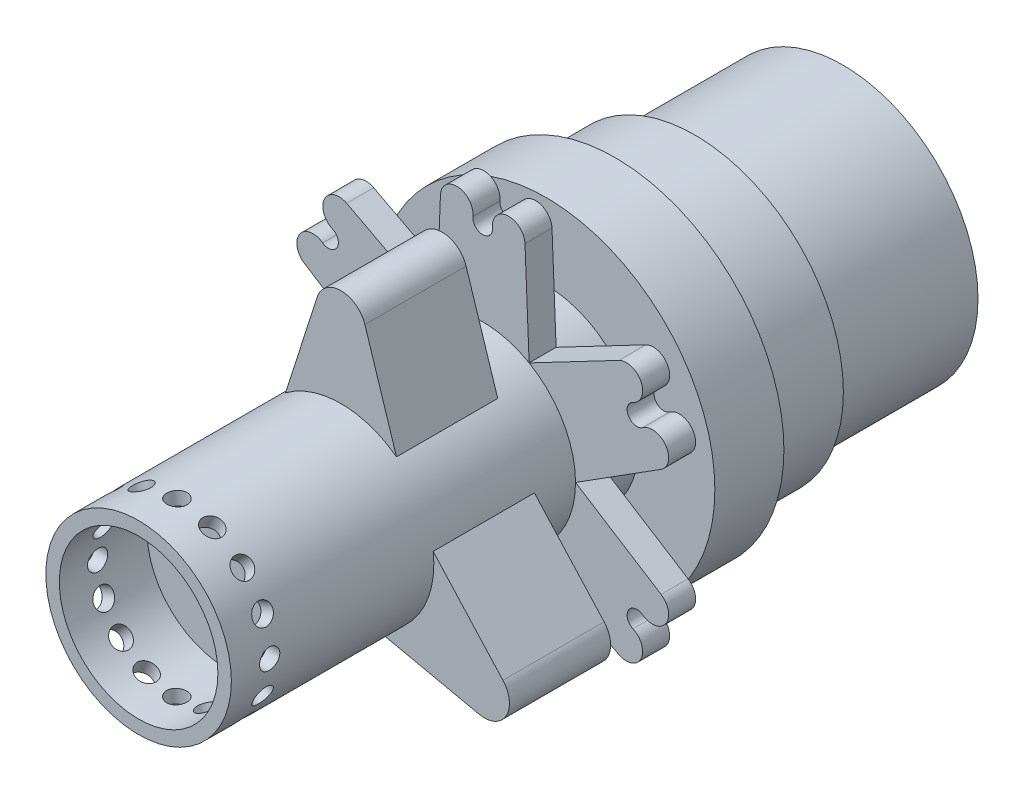
SolidWorks part; units mm, degrees
ref_plane "Front Plane" through (0, 0, 0) normal (0, 0, 1) x (1, 0, 0)
ref_plane "Top Plane" through (0, 0, 0) normal (0, 1, 0) x (1, 0, 0)
ref_plane "Right Plane" through (0, 0, 0) normal (1, 0, 0) x (0, 0, -1)
sketch "Sketch1" plane through (0, 0, 0) normal (0, 0, 1) x (1, 0, 0)
  circle A0 centre (0, 0) radius 17.4625
  dimension "D1" = 34.925
extrude "Boss-Extrude1" add sketch "Sketch1" along normal blind 132.588
ref_axis "Axis1" through (0, 0, 187.0777) along (0, 0, -1)
ref_plane "Wheel Center Mount Plane" through (0, 0, 94.488) normal (0, 0, 1) x (1, 0, 0)
ref_plane "Brake Rotor Mount Plane" through (0, 0, 62.738) normal (0, 0, 1) x (1, 0, 0)
sketch "Sketch3" plane through (0, 0, 94.488) normal (0, 0, 1) x (1, 0, 0)
  line L0 (10.4424, 13.9962) -> (4.4896, 32.5879)
  line L1 (-10.4424, 13.9962) -> (-4.4896, 32.5879)
  line L2 (17.3423, 2.0453) -> (30.4667, -12.4058)
  line L3 (6.8999, -16.0415) -> (25.9771, -20.182)
  line L4 (-6.8999, -16.0415) -> (-25.9771, -20.182)
  line L5 (-17.3423, 2.0453) -> (-30.4667, -12.4058)
  line L6 (0, 0) -> (10.4424, 13.9962) construction
  line L7 (0, 0) -> (6.8999, -16.0415) construction
  arc A0 (4.4896, 32.5879) -> (-4.4896, 32.5879) centre (0, 31.1504) ccw
  circle A1 centre (0, 0) radius 17.4625
  arc A2 (10.4424, 13.9962) -> (-10.4424, 13.9962) centre (0, 0) ccw
  circle A3 centre (0, 0) radius 17.4625 construction
  arc A4 (25.9771, -20.182) -> (30.4667, -12.4058) centre (26.977, -15.5752) ccw
  arc A5 (-30.4667, -12.4058) -> (-25.9771, -20.182) centre (-26.977, -15.5752) ccw
  arc A6 (-17.3423, 2.0453) -> (-6.8999, -16.0415) centre (0, 0) ccw
  arc A7 (6.8999, -16.0415) -> (17.3423, 2.0453) centre (0, 0) ccw
  dimension "D3" = 120
  dimension "D1" = 0
  dimension "D2" = 3
extrude "Boss-Extrude2" add sketch "Sketch3" against normal blind 19.05 contours A7 L3 A4 L2 | A2 L0 A0 L1 | L5 A5 L4 A6
sketch "Sketch4" plane through (0, 0, 62.738) normal (0, 0, 1) x (1, 0, 0)
  line L0 (8.7313, 15.123) -> (7.9569, 34.1622)
  line L1 (0, 0) -> (0, 40.5034) construction
  line L2 (-4.3369, 31.6625) -> (4.3369, 31.6625) construction
  line L3 (-8.7312, 15.123) -> (-7.9569, 34.1622)
  line L4 (17.4625, 0) -> (33.5638, 10.1902)
  line L5 (8.7313, 15.123) -> (25.6068, 23.972)
  line L6 (8.7313, -15.123) -> (25.6068, -23.972)
  line L7 (17.4625, 0) -> (33.5638, -10.1902)
  line L8 (-8.7312, -15.123) -> (-7.9569, -34.1622)
  line L9 (8.7313, -15.123) -> (7.9569, -34.1622)
  line L10 (-17.4625, 0) -> (-33.5638, -10.1902)
  line L11 (-8.7312, -15.123) -> (-25.6068, -23.972)
  line L12 (-8.7312, 15.123) -> (-25.6068, 23.972)
  line L13 (-17.4625, 0) -> (-33.5638, 10.1902)
  arc A0 (7.9569, 34.1622) -> (1.8381, 33.709) centre (4.89, 34.0374) ccw
  arc A1 (1.8381, 33.709) -> (-1.8381, 33.709) centre (0, 33.5112) cw
  arc A2 (-7.9569, 34.1622) -> (-1.8381, 33.709) centre (-4.89, 34.0374) cw
  circle A3 centre (0, 0) radius 17.4625 construction
  arc A4 (33.5638, 10.1902) -> (30.1119, 15.2627) centre (31.9223, 12.7839) ccw
  arc A5 (30.1119, 15.2627) -> (28.2738, 18.4463) centre (29.0216, 16.7556) cw
  arc A6 (25.6068, 23.972) -> (28.2738, 18.4463) centre (27.0323, 21.2535) cw
  arc A7 (25.6068, -23.972) -> (28.2738, -18.4463) centre (27.0323, -21.2535) ccw
  arc A8 (28.2738, -18.4463) -> (30.1119, -15.2627) centre (29.0216, -16.7556) cw
  arc A9 (33.5638, -10.1902) -> (30.1119, -15.2627) centre (31.9223, -12.7839) cw
  arc A10 (-7.9569, -34.1622) -> (-1.8381, -33.709) centre (-4.89, -34.0374) ccw
  arc A11 (-1.8381, -33.709) -> (1.8381, -33.709) centre (0, -33.5112) cw
  arc A12 (7.9569, -34.1622) -> (1.8381, -33.709) centre (4.89, -34.0374) cw
  arc A13 (-33.5638, -10.1902) -> (-30.1119, -15.2627) centre (-31.9223, -12.7839) ccw
  arc A14 (-30.1119, -15.2627) -> (-28.2738, -18.4463) centre (-29.0216, -16.7556) cw
  arc A15 (-25.6068, -23.972) -> (-28.2738, -18.4463) centre (-27.0323, -21.2535) cw
  arc A16 (-25.6068, 23.972) -> (-28.2738, 18.4463) centre (-27.0323, 21.2535) ccw
  arc A17 (-28.2738, 18.4463) -> (-30.1119, 15.2627) centre (-29.0216, 16.7556) cw
  arc A18 (-33.5638, 10.1902) -> (-30.1119, 15.2627) centre (-31.9223, 12.7839) cw
  arc A19 (6.8999, -16.0415) -> (17.3423, 2.0453) centre (0, 0) ccw construction
  circle A20 centre (0, 0) radius 17.4625
  point P65 (0, 0)
  dimension "D1" = 6
extrude "Boss-Extrude3" add sketch "Sketch4" along normal blind 5.08 contours L5 A6 A5 A4 L4 L7 A9 A8 A7 L6 L9 A12 A11 A10 L8 L11 A15 A14 A13 L10 L13 A18 A17 A16 L12 L3 A2 A1 A0 L0
sketch "Sketch5" plane through (0, 0, 132.588) normal (0, 0, 1) x (1, 0, 0)
  circle A0 centre (0, 0) radius 14.9225
  circle A1 centre (0, 0) radius 17.4625 construction
  dimension "D1" = 2.54
extrude "Cut-Extrude1" cut sketch "Sketch5" against normal blind 16.51
sketch "Sketch7" plane through (0, 0, 0) normal (0, 1, 0) x (1, 0, 0)
  line L0 (0, -144.2543) -> (0, -120.9217) construction
  line L1 (-17.4625, -132.588) -> (17.4625, -132.588) construction
  circle A0 centre (0, -125.3787) radius 1.905
  point P6 (0, -132.588)
  dimension "D1" = 3.81
extrude "Cut-Extrude2" cut sketch "Sketch7" along normal up to surface (17.4625 mm away)
pattern_circular "CirPattern1" count 16 over 360 about axis through (0, 0, 187.0777) along (0, 0, -1) of "Cut-Extrude2"
ref_plane "Plane1" through (0, 0, 55.88) normal (0, 0, 1) x (1, 0, 0)
sketch "Sketch8" plane through (0, 0, 55.88) normal (0, 0, 1) x (1, 0, 0)
  circle A0 centre (0, 0) radius 31.75
  circle A1 centre (0, 0) radius 17.4625 construction
  dimension "D1" = 63.5
extrude "Boss-Extrude4" add sketch "Sketch8" against normal blind 13
sketch "Sketch9" plane through (0, 0, 0) normal (0, 0, 1) x (1, 0, 0)
  circle A0 centre (0, 0) radius 27.94
  dimension "D1" = 55.88
extrude "Boss-Extrude5" add sketch "Sketch9" against normal blind 15 from surface at 42.88 starting at face at (17.4625, 0, 42.88)
sketch "Sketch10" plane through (0, 0, 0) normal (0, 0, 1) x (1, 0, 0)
  circle A0 centre (0, 0) radius 25.4
  dimension "D1" = 50.8
extrude "Boss-Extrude6" add sketch "Sketch10" along normal up to surface (27.88 mm away) up to face at (17.4625, 0, 27.88)
